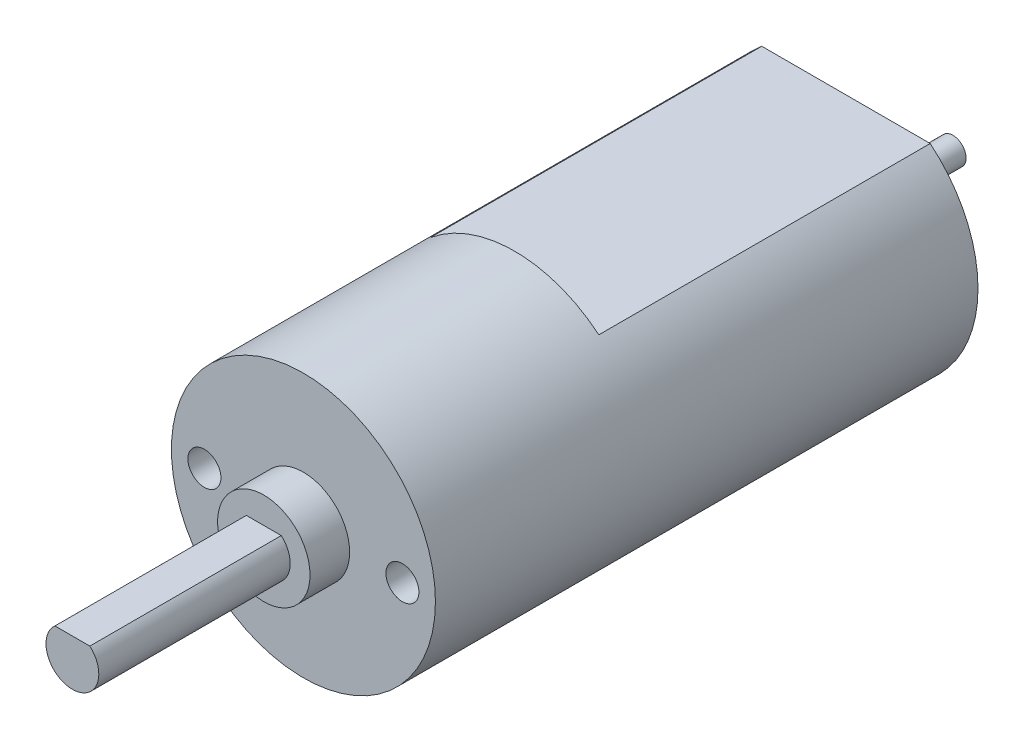
SolidWorks part; units mm, degrees
ref_plane "Front Plane" through (0, 0, 0) normal (0, 0, 1) x (1, 0, 0)
ref_plane "Top Plane" through (0, 0, 0) normal (0, 1, 0) x (1, 0, 0)
ref_plane "Right Plane" through (0, 0, 0) normal (1, 0, 0) x (0, 0, -1)
sketch "Sketch1" plane through (0, 0, 0) normal (0, 0, 1) x (1, 0, 0)
  circle A0 centre (0, 0) radius 10
  dimension "D1" = 20
extrude "Boss-Extrude1" add sketch "Sketch1" against normal blind 41.1
sketch "Sketch2" plane through (0, 0, 0) normal (1, 0, 0) x (0, 0, -1)
  line L0 (41.1, 10) -> (0, 10) construction
  line L1 (16, 10) -> (41.1, 10)
  line L2 (16, 10) -> (16, 7.7)
  line L3 (16, 7.7) -> (41.1, 7.7)
  line L4 (41.1, 10) -> (41.1, 7.7)
  line L5 (41.1, -10) -> (41.1, 10) construction
  line L6 (11, 0) -> (-11, 0) construction
  dimension "D1" = 7.7
  dimension "D2" = 25.1
extrude "Cut-Extrude1" cut sketch "Sketch2" against normal through all both and the other way through all
mirror "Mirror1" about plane through (0, 0, 0) normal (0, 1, 0) of "Cut-Extrude1"
sketch "Sketch3" plane through (0, 0, 0) normal (0, 0, 1) x (1, 0, 0)
  circle A0 centre (0, 0) radius 3.5
  dimension "D1" = 7
extrude "Boss-Extrude2" add sketch "Sketch3" along normal blind 3
sketch "Sketch5" plane through (0, 0, 3) normal (0, 0, 1) x (1, 0, 0)
  circle A0 centre (0, 0) radius 2
  dimension "D1" = 4
extrude "Boss-Extrude4" add sketch "Sketch5" along normal blind 14.5
sketch "Sketch6" plane through (0, 0, 0) normal (1, 0, 0) x (0, 0, -1)
  line L0 (-3, 3.5) -> (-3, -3.5) construction
  line L1 (-17.5, 2) -> (-3, 2)
  line L2 (-17.5, 2) -> (-17.5, 1.5)
  line L3 (-17.5, 1.5) -> (-3, 1.5)
  line L4 (-3, 2) -> (-3, 1.5)
  dimension "D1" = 3.5
extrude "Cut-Extrude2" cut sketch "Sketch6" against normal through all both and the other way through all
sketch "Sketch7" plane through (0, 0, -41.1) normal (0, 0, -1) x (-1, 0, 0)
  circle A0 centre (0, 0) radius 3.1
  dimension "D1" = 6.2
extrude "Boss-Extrude5" add sketch "Sketch7" along normal blind 2.1
sketch "Sketch8" plane through (0, 0, -43.2) normal (0, 0, -1) x (-1, 0, 0)
  circle A0 centre (0, 0) radius 1
  dimension "D1" = 2
extrude "Boss-Extrude6" add sketch "Sketch8" along normal blind 6
sketch "Sketch10" plane through (0, 0, 0) normal (0, 0, 1) x (1, 0, 0)
  line L0 (11, 0) -> (-11, 0) construction
  line L1 (0, -11) -> (0, 11) construction
  circle A0 centre (-7.5, 0) radius 1.25
  dimension "D2" = 2.5
  dimension "D1" = 7.5
extrude "Cut-Extrude3" cut sketch "Sketch10" against normal blind 15
mirror "Mirror2" about plane through (0, 0, 0) normal (1, 0, 0) of "Cut-Extrude3"
